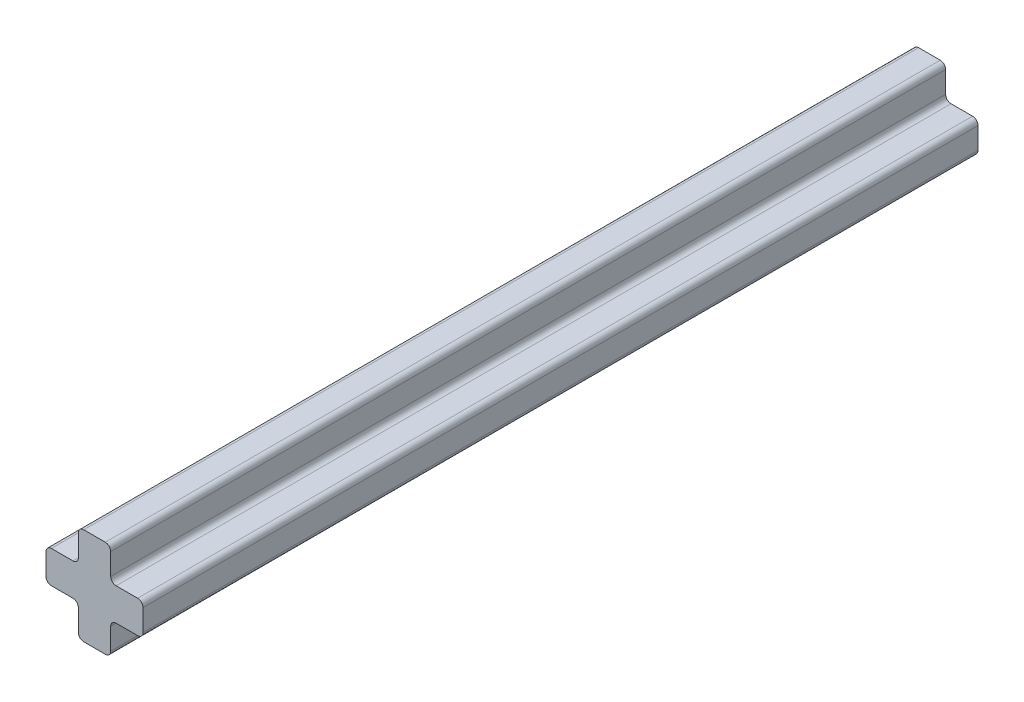
SolidWorks part; units mm, degrees
material "ABS PC"
ref_plane "Front Plane" through (0, 0, 0) normal (0, 0, 1) x (1, 0, 0)
ref_plane "Top Plane" through (0, 0, 0) normal (0, 1, 0) x (1, 0, 0)
ref_plane "Right Plane" through (0, 0, 0) normal (1, 0, 0) x (0, 0, -1)
sketch "Sketch1" plane through (0, 0, 0) normal (0, 0, 1) x (1, 0, 0)
  line L0 (-0.762, 2.032) -> (-0.762, 1.016)
  line L1 (-1.016, 0.762) -> (-2.032, 0.762)
  line L2 (-2.286, 0.508) -> (-2.286, -0.508)
  line L3 (-2.032, -0.762) -> (-1.016, -0.762)
  line L4 (-0.762, -1.016) -> (-0.762, -2.032)
  line L5 (-0.508, -2.286) -> (0.508, -2.286)
  line L6 (0.762, -2.032) -> (0.762, -1.016)
  line L7 (1.016, -0.762) -> (2.032, -0.762)
  line L8 (2.286, -0.508) -> (2.286, 0.508)
  line L9 (2.032, 0.762) -> (1.016, 0.762)
  line L10 (0.762, 1.016) -> (0.762, 2.032)
  line L11 (0.508, 2.286) -> (-0.508, 2.286)
  line L12 (0, -22.3743) -> (0, 22.3743) construction
  line L13 (39.1001, 0) -> (-39.1001, 0) construction
  arc A0 (-0.762, 1.016) -> (-1.016, 0.762) centre (-1.016, 1.016) cw
  arc A1 (-0.762, 2.032) -> (-0.508, 2.286) centre (-0.508, 2.032) cw
  arc A2 (0.508, 2.286) -> (0.762, 2.032) centre (0.508, 2.032) cw
  arc A3 (0.762, 1.016) -> (1.016, 0.762) centre (1.016, 1.016) ccw
  arc A4 (2.032, 0.762) -> (2.286, 0.508) centre (2.032, 0.508) cw
  arc A5 (2.032, -0.762) -> (2.286, -0.508) centre (2.032, -0.508) ccw
  arc A6 (1.016, -0.762) -> (0.762, -1.016) centre (1.016, -1.016) ccw
  arc A7 (0.762, -2.032) -> (0.508, -2.286) centre (0.508, -2.032) cw
  arc A8 (-0.508, -2.286) -> (-0.762, -2.032) centre (-0.508, -2.032) cw
  arc A9 (-1.016, -0.762) -> (-0.762, -1.016) centre (-1.016, -1.016) cw
  arc A10 (-2.032, -0.762) -> (-2.286, -0.508) centre (-2.032, -0.508) cw
  arc A11 (-2.286, 0.508) -> (-2.032, 0.762) centre (-2.032, 0.508) cw
  point P40 (0, 0)
  dimension "D6" = 0.254
  dimension "D1" = 4.572
  dimension "D2" = 4.572
  dimension "D3" = 1.524
  dimension "D4" = 1.524
  dimension "D5" = 1.524
extrude "Extrude1" add sketch "Sketch1" along normal blind 39.325
